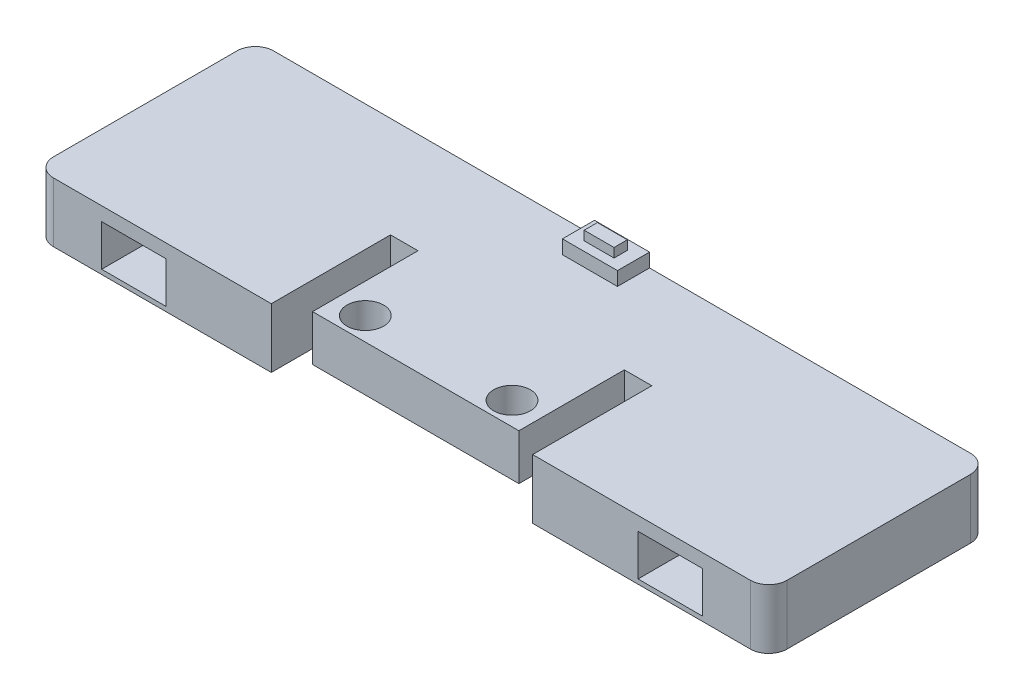
SolidWorks part; units mm, degrees
ref_plane "前视基准面" through (0, 0, 0) normal (0, 0, 1) x (1, 0, 0)
ref_plane "上视基准面" through (0, 0, 0) normal (0, 1, 0) x (1, 0, 0)
ref_plane "右视基准面" through (0, 0, 0) normal (1, 0, 0) x (0, 0, -1)
other "Configuration Table"
sketch "草图1" plane through (0, 0, 0) normal (0, 1, 0) x (1, 0, 0)
  line L1 (-40, -12) -> (40, -12)
  line L2 (-40, -12) -> (-40, 12)
  line L3 (-40, 12) -> (40, 12)
  line L4 (40, -12) -> (40, 12)
  line L5 (-40, -12) -> (40, 12) construction
  line L6 (-40, 12) -> (40, -12) construction
  point P0 (0, 0)
  dimension "D1" = 80
  dimension "D2" = 24
extrude "凸台-拉伸1" add sketch "草图1" along normal blind 6.5
sketch "草图2" plane through (0, 6.5, 0) normal (0, 1, 0) x (1, 0, 0)
  line L0 (40, 12) -> (-40, 12) construction
  line L1 (-3, 8.5) -> (3, 8.5)
  line L2 (-3, 8.5) -> (-3, 12)
  line L3 (-3, 12) -> (3, 12)
  line L4 (3, 8.5) -> (3, 12)
  line L5 (-3, 8.5) -> (3, 12) construction
  line L6 (-3, 12) -> (3, 8.5) construction
  point P0 (0, 10.25)
  dimension "D1" = 6
  dimension "D2" = 3.5
extrude "凸台-拉伸2" add sketch "草图2" along normal blind 1.5
sketch "草图3" plane through (0, 8, 0) normal (0, 1, 0) x (1, 0, 0)
  line L1 (-1.63, 10.9468) -> (1.63, 10.9468)
  line L2 (-1.63, 10.9468) -> (-1.63, 9.4979)
  line L3 (-1.63, 9.4979) -> (1.63, 9.4979)
  line L4 (1.63, 10.9468) -> (1.63, 9.4979)
  line L5 (-1.63, 10.9468) -> (1.63, 9.4979) construction
  line L6 (-1.63, 9.4979) -> (1.63, 10.9468) construction
  point P0 (0, 10.2223)
extrude "凸台-拉伸3" add sketch "草图3" along normal blind 1
sketch "草图4" plane through (0, 6.5, 0) normal (0, 1, 0) x (1, 0, 0)
  line L0 (-14.25, -12) -> (-14.25, 1)
  line L1 (-40, -12) -> (40, -12) construction
  line L2 (-14.25, 1) -> (-11.25, 1)
  line L3 (-11.25, 1) -> (-11.25, -10.5)
  line L4 (-11.25, -12) -> (-14.25, -12)
  line L5 (0, 0) -> (0, -12) construction
  line L6 (-11.25, -10.5) -> (11.25, -10.5)
  line L7 (11.25, -12) -> (-11.25, -12)
  line L8 (11.25, -12) -> (14.25, -12)
  line L9 (11.25, 1) -> (11.25, -10.5)
  line L10 (14.25, 1) -> (11.25, 1)
  line L11 (14.25, -12) -> (14.25, 1)
  circle A0 centre (-8, -8) radius 2
  circle A1 centre (8, -8) radius 2
  point P16 (0, -10.5)
  dimension "D2" = 4
  dimension "D7" = 4
  dimension "D1" = 8
  dimension "D3" = 11.25
  dimension "D4" = 3
  dimension "D5" = 13
  dimension "D6" = 1.5
extrude "切除-拉伸1" cut sketch "草图4" against normal through all
sketch "草图5" plane through (0, 0, 12) normal (0, 0, 1) x (1, 0, 0)
  line L1 (-25.75, 5) -> (-32.75, 5)
  line L2 (-25.75, 5) -> (-25.75, 0.5)
  line L3 (-25.75, 0.5) -> (-32.75, 0.5)
  line L4 (-32.75, 5) -> (-32.75, 0.5)
  line L5 (-25.75, 5) -> (-32.75, 0.5) construction
  line L6 (-25.75, 0.5) -> (-32.75, 5) construction
  line L12 (-14.25, 0) -> (-14.25, 6.5) construction
  line L13 (0, 0) -> (0, 6.5) construction
  line L14 (11.25, 6.5) -> (-11.25, 6.5) construction
  line L15 (25.75, 0.5) -> (32.75, 5) construction
  line L16 (25.75, 5) -> (32.75, 0.5) construction
  line L17 (32.75, 5) -> (32.75, 0.5)
  line L18 (25.75, 0.5) -> (32.75, 0.5)
  line L19 (25.75, 5) -> (25.75, 0.5)
  line L20 (25.75, 5) -> (32.75, 5)
  line L21 (-40, 0) -> (-14.25, 0) construction
  point P0 (-29.25, 2.75)
  dimension "D1" = 7
  dimension "D2" = 4.5
  dimension "D3" = 11.5
  dimension "D4" = 0.5
extrude "切除-拉伸2" cut sketch "草图5" against normal blind 6
sketch "草图6" plane through (0, 0, 0) normal (0, -1, 0) x (1, 0, 0)
  line L1 (-14.25, 12) -> (14.25, 12)
  line L2 (-14.25, 12) -> (-14.25, -1)
  line L3 (-14.25, -1) -> (14.25, -1)
  line L4 (14.25, 12) -> (14.25, -1)
  line L5 (-14.25, 12) -> (14.25, -1) construction
  line L6 (-14.25, -1) -> (14.25, 12) construction
  point P4 (0, 5.5)
extrude "切除-拉伸3" cut sketch "草图6" against normal blind 1.5
sketch "草图7" plane through (0, 0, 0) normal (0, -1, 0) x (1, 0, 0)
  line L0 (0, 0) -> (0, -12) construction
  line L1 (-34.6715, -7.9005) -> (-31.2542, -7.9005)
  line L2 (-34.6715, -7.9005) -> (-34.6715, -10.9191)
  line L3 (-34.6715, -10.9191) -> (-31.2542, -10.9191)
  line L4 (-31.2542, -7.9005) -> (-31.2542, -10.9191)
  line L5 (-34.6715, -7.9005) -> (-31.2542, -10.9191) construction
  line L6 (-34.6715, -10.9191) -> (-31.2542, -7.9005) construction
  line L7 (-11.9536, -7.6591) -> (-9.418, -7.6591)
  line L8 (-11.9536, -7.6591) -> (-11.9536, -10.3154)
  line L9 (-11.9536, -10.3154) -> (-9.418, -10.3154)
  line L10 (-9.418, -7.6591) -> (-9.418, -10.3154)
  line L11 (-11.9536, -7.6591) -> (-9.418, -10.3154) construction
  line L12 (-11.9536, -10.3154) -> (-9.418, -7.6591) construction
  line L13 (40, -12) -> (-40, -12) construction
  line L14 (11.9536, -10.3154) -> (9.418, -7.6591) construction
  line L15 (11.9536, -7.6591) -> (9.418, -10.3154) construction
  line L16 (34.6715, -10.9191) -> (31.2542, -7.9005) construction
  line L17 (34.6715, -7.9005) -> (31.2542, -10.9191) construction
  line L18 (9.418, -7.6591) -> (9.418, -10.3154)
  line L19 (11.9536, -10.3154) -> (9.418, -10.3154)
  line L20 (11.9536, -7.6591) -> (11.9536, -10.3154)
  line L21 (11.9536, -7.6591) -> (9.418, -7.6591)
  line L22 (31.2542, -7.9005) -> (31.2542, -10.9191)
  line L23 (34.6715, -10.9191) -> (31.2542, -10.9191)
  line L24 (34.6715, -7.9005) -> (34.6715, -10.9191)
  line L25 (34.6715, -7.9005) -> (31.2542, -7.9005)
  circle A0 centre (-32.9629, -4.7612) radius 1.7086
  circle A1 centre (-10.6858, -4.7612) radius 1.6311
  circle A2 centre (10.6858, -4.7612) radius 1.6311
  circle A3 centre (32.9629, -4.7612) radius 1.7086
  point P3 (-32.9629, -9.4098)
  point P9 (-10.6858, -8.9872)
  point P31 (10.6858, -8.9872)
  point P32 (32.9629, -9.4098)
extrude "切除-拉伸4" cut sketch "草图7" against normal blind 1
fillet "圆角1" radius 2 4 edges at (40, 3.25, 12) (40, 3.25, -12) (-40, 3.25, -12) (-40, 3.25, 12)
